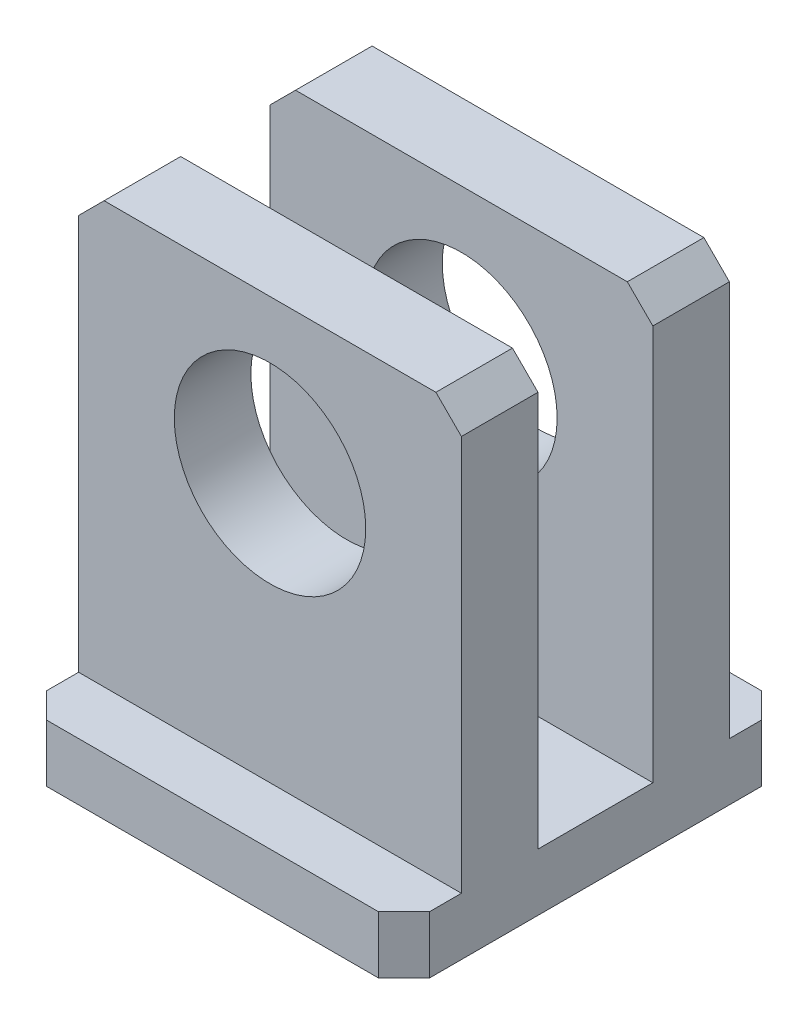
SolidWorks part; units mm, degrees
ref_plane "前视基准面" through (0, 0, 0) normal (0, 0, 1) x (1, 0, 0)
ref_plane "上视基准面" through (0, 0, 0) normal (0, 1, 0) x (1, 0, 0)
ref_plane "右视基准面" through (0, 0, 0) normal (1, 0, 0) x (0, 0, -1)
other "Configuration Table"
sketch "草图1" plane through (0, 0, 0) normal (0, 1, 0) x (1, 0, 0)
  line L0 (-15, 13) -> (-13, 15)
  line L1 (-13, -15) -> (13, -15)
  line L2 (-15, -13) -> (-15, 13)
  line L3 (-13, 15) -> (13, 15)
  line L4 (15, -13) -> (15, 13)
  line L5 (-15, -15) -> (15, 15) construction
  line L6 (-15, 15) -> (15, -15) construction
  line L7 (13, 15) -> (15, 13)
  line L8 (13, -15) -> (15, -13)
  line L9 (-15, -13) -> (-13, -15)
  point P0 (0, 0)
  dimension "D1" = 30
  dimension "D2" = 30
extrude "凸台-拉伸1" add sketch "草图1" along normal blind 4.5
sketch "草图2" plane through (0, 4.5, 0) normal (0, 1, 0) x (1, 0, 0)
  line L0 (15, -13) -> (15, 13) construction
  line L1 (-15, 10.5) -> (15, 10.5)
  line L2 (-15, 10.5) -> (-15, -10.5)
  line L3 (-15, -10.5) -> (15, -10.5)
  line L4 (15, 10.5) -> (15, -10.5)
  line L5 (-15, 10.5) -> (15, -10.5) construction
  line L6 (-15, -10.5) -> (15, 10.5) construction
  point P0 (0, 0)
  dimension "D1" = 21
extrude "凸台-拉伸2" add sketch "草图2" along normal blind 33
sketch "草图3" plane through (0, 37.5, 0) normal (0, 1, 0) x (1, 0, 0)
  line L0 (15, -10.5) -> (15, 10.5) construction
  line L1 (-15, 4.5) -> (15, 4.5)
  line L2 (-15, 4.5) -> (-15, -4.5)
  line L3 (-15, -4.5) -> (15, -4.5)
  line L4 (15, 4.5) -> (15, -4.5)
  line L5 (-15, 4.5) -> (15, -4.5) construction
  line L6 (-15, -4.5) -> (15, 4.5) construction
  point P0 (0, 0)
  dimension "D1" = 9
extrude "切除-拉伸1" cut sketch "草图3" against normal blind 33
sketch "草图4" plane through (0, 0, 10.5) normal (0, 0, 1) x (1, 0, 0)
  circle A0 centre (0, 25.5) radius 7.5
  dimension "D2" = 15
  dimension "D1" = 25.5
extrude "切除-拉伸2" cut sketch "草图4" against normal through all
sketch "草图9" plane through (0, 0, 10.5) normal (0, 0, 1) x (1, 0, 0)
  line L0 (-15, 35.5) -> (-13, 37.5)
  line L1 (13, 37.5) -> (15, 35.5)
  line L2 (-13, 37.5) -> (-15, 37.5)
  line L4 (-15, 4.5) -> (15, 4.5)
  line L5 (15, 4.5) -> (15, 37.5)
  line L6 (15, 37.5) -> (-15, 37.5)
  line L7 (-15, 37.5) -> (-15, 4.5)
  line L9 (15, 35.5) -> (15, 37.5)
  line L10 (15, 37.5) -> (13, 37.5)
  line L11 (-15, 37.5) -> (-15, 35.5)
  dimension "D2" = 2
  dimension "D3" = 2
  dimension "D4" = 2
  dimension "D5" = 2
  dimension "D1" = 0
extrude "切除-拉伸6" cut sketch "草图9" against normal through all
